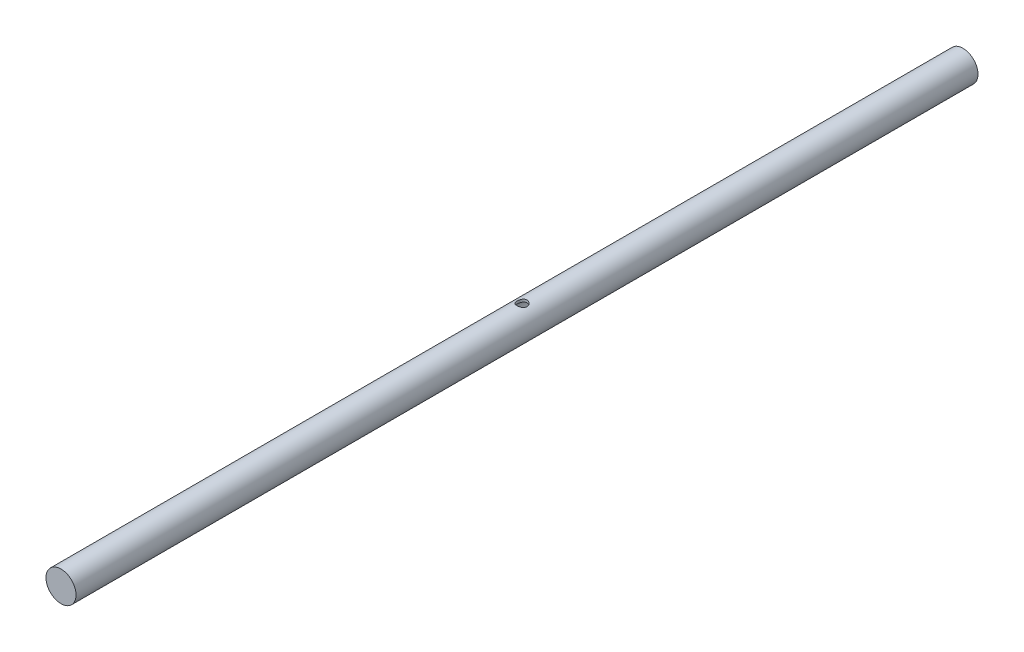
SolidWorks part; units mm, degrees
ref_plane "Front Plane" through (0, 0, 0) normal (0, 0, 1) x (1, 0, 0)
ref_plane "Top Plane" through (0, 0, 0) normal (0, 1, 0) x (1, 0, 0)
ref_plane "Right Plane" through (0, 0, 0) normal (1, 0, 0) x (0, 0, -1)
sketch "Sketch1" plane through (0, 0, 0) normal (0, 0, 1) x (1, 0, 0)
  circle A0 centre (0, 0) radius 3.81
  dimension "D1" = 7.62
extrude "Boss-Extrude1" add sketch "Sketch1" along normal blind 228.6
ref_plane "Plane1" through (0, 0, 114.3) normal (0, 0, 1) x (1, 0, 0)
shell "Shell1" thickness 0.635
sketch "Sketch3" plane through (0, 0, 0) normal (0, 1, 0) x (1, 0, 0)
  line L1 (-4.191, -114.3) -> (4.191, -114.3) construction
  circle A0 centre (0, -111.76) radius 1.27
  point P2 (0, -104.7666)
  point P4 (0, 0)
  dimension "D1" = 2.54
  dimension "D2" = 2.54
extrude "Cut-Extrude3" cut sketch "Sketch3" along normal blind 5.08
